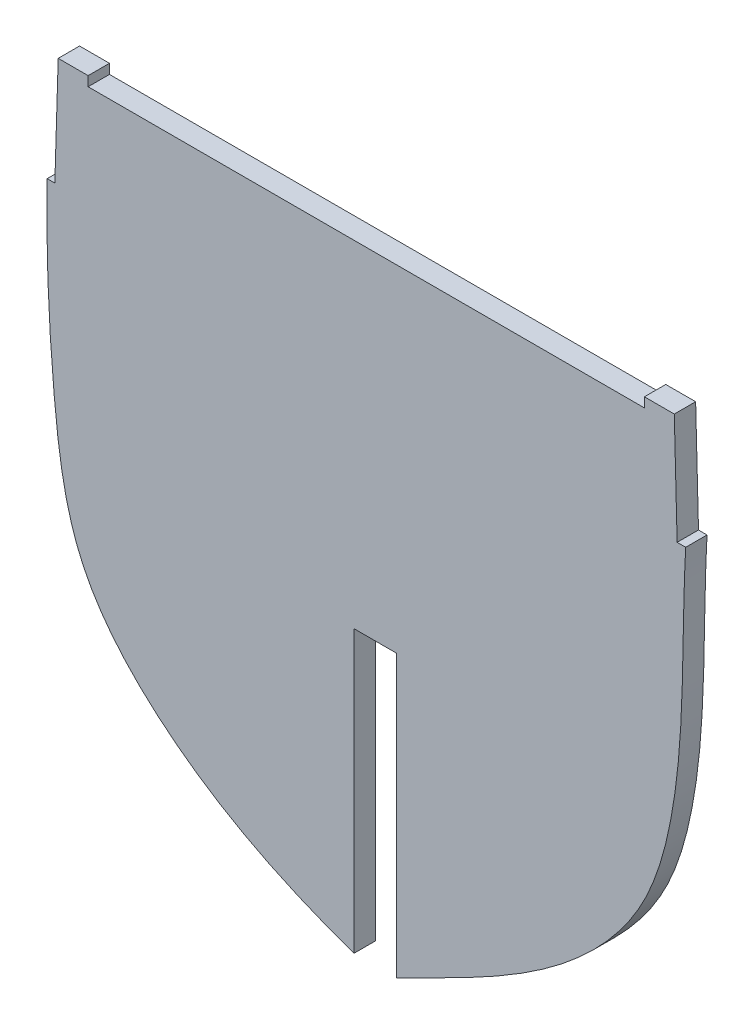
SolidWorks part; units mm, degrees
ref_plane "前视基准面" through (0, 0, 0) normal (0, 0, 1) x (1, 0, 0)
ref_plane "上视基准面" through (0, 0, 0) normal (0, 1, 0) x (1, 0, 0)
ref_plane "右视基准面" through (0, 0, 0) normal (1, 0, 0) x (0, 0, -1)
other "Configuration Table"
sketch "草图1" plane through (0, 0, 0) normal (0, 0, 1) x (1, 0, 0)
  line L0 (376.6667, 613.5) -> (1883.3333, 613.5) construction
  line L25 (24.545, 177.486) -> (128.7483, 177.486)
  line L26 (128.7483, 177.486) -> (128.7483, 179.2933)
  line L27 (128.7483, 179.2933) -> (134.346, 179.2933)
  line L28 (134.346, 179.2933) -> (134.8799, 158.746)
  line L29 (134.8799, 158.746) -> (136.4802, 158.746)
  line L30 (24.545, 177.486) -> (24.545, 179.2933)
  line L31 (24.545, 179.2933) -> (18.9383, 179.2933)
  line L32 (18.9383, 179.2933) -> (18.3105, 158.746)
  line L33 (18.3105, 158.746) -> (16.8755, 158.746)
  line L34 (74.3394, 61.7996) -> (74.3394, 114.4779)
  line L35 (74.3394, 114.4779) -> (82.3392, 114.4779)
  line L36 (82.3392, 114.4779) -> (82.3392, 61.7996)
  spline S7 degree 3 poles (16.8755, 158.746) (16.6568, 146.6168) (17.4738, 127.0581) (21.2698, 98.6479) (41.891, 75.8023) (61.332, 66.3642) (74.3394, 61.7996) knots 0 0 0 0 0.287579 0.483998 0.667834 1 1 1 1
  spline S8 degree 3 poles (82.3392, 61.7996) (93.4138, 67.4011) (111.7332, 75.7213) (128.9444, 95.0471) (136.9138, 122.3684) (135.613, 143.3086) (136.4802, 158.746) knots 0 0 0 0 0.307761 0.49025 0.61633 1 1 1 1
  dimension "D1" = 7.9999
  dimension "D2" = 52.6783
extrude "凸台-拉伸1" add sketch "草图1" along normal blind 4
